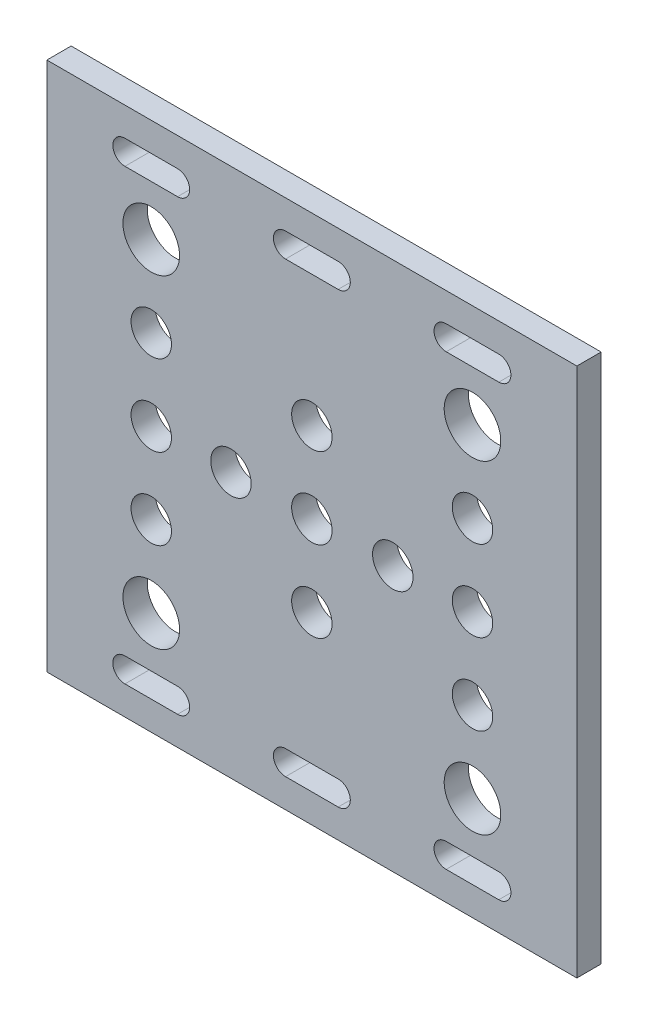
SolidWorks part; units mm, degrees
ref_plane "Front Plane" through (0, 0, 0) normal (0, 0, 1) x (1, 0, 0)
ref_plane "Top Plane" through (0, 0, 0) normal (0, 1, 0) x (1, 0, 0)
ref_plane "Right Plane" through (0, 0, 0) normal (1, 0, 0) x (0, 0, -1)
sketch "Sketch1" plane through (0, 0, 0) normal (0, 0, 1) x (1, 0, 0)
  line L0 (-32.75, -27.7) -> (32.75, -27.7) construction
  line L1 (-32.75, -32.75) -> (32.75, -32.75)
  line L2 (-32.75, -32.75) -> (-32.75, 32.75)
  line L3 (-32.75, 32.75) -> (32.75, 32.75)
  line L4 (32.75, -32.75) -> (32.75, 32.75)
  line L5 (-32.75, -32.75) -> (32.75, 32.75) construction
  line L6 (-32.75, 32.75) -> (32.75, -32.75) construction
  line L7 (-19.85, 32.75) -> (-19.85, -32.75) construction
  line L8 (0, 48.3783) -> (0, -50.4998) construction
  line L9 (-32.75, 27.7) -> (32.75, 27.7) construction
  line L10 (-23.1, 27.7) -> (-16.6, 27.7) construction
  line L11 (-23.1, 29.2) -> (-16.6, 29.2)
  line L12 (-23.1, 26.2) -> (-16.6, 26.2)
  line L13 (-32.75, 0) -> (32.75, 0) construction
  line L14 (-23.1, -27.7) -> (-16.6, -27.7) construction
  line L15 (-23.1, -26.2) -> (-16.6, -26.2)
  line L16 (-23.1, -29.2) -> (-16.6, -29.2)
  line L17 (-3.25, 27.7) -> (3.25, 27.7) construction
  line L18 (-3.25, 29.2) -> (3.25, 29.2)
  line L19 (-3.25, 26.2) -> (3.25, 26.2)
  line L20 (-3.25, -27.7) -> (3.25, -27.7) construction
  line L21 (-3.25, -29.2) -> (3.25, -29.2)
  line L22 (-3.25, -26.2) -> (3.25, -26.2)
  line L23 (23.1, -27.7) -> (16.6, -27.7) construction
  line L24 (23.1, -26.2) -> (16.6, -26.2)
  line L25 (23.1, -29.2) -> (16.6, -29.2)
  line L26 (23.1, 27.7) -> (16.6, 27.7) construction
  line L27 (23.1, 29.2) -> (16.6, 29.2)
  line L28 (23.1, 26.2) -> (16.6, 26.2)
  circle A0 centre (-19.85, 20) radius 3.5
  circle A1 centre (-19.85, 10) radius 2.5
  circle A2 centre (-19.85, 0) radius 2.5
  circle A3 centre (-19.85, -10) radius 2.5
  circle A4 centre (-19.85, -20) radius 3.5
  arc A5 (-23.1, 29.2) -> (-23.1, 26.2) centre (-23.1, 27.7) ccw
  arc A6 (-16.6, 26.2) -> (-16.6, 29.2) centre (-16.6, 27.7) ccw
  arc A7 (-23.1, -26.2) -> (-23.1, -29.2) centre (-23.1, -27.7) ccw
  arc A8 (-16.6, -29.2) -> (-16.6, -26.2) centre (-16.6, -27.7) ccw
  arc A9 (-3.25, 29.2) -> (-3.25, 26.2) centre (-3.25, 27.7) ccw
  arc A10 (3.25, 26.2) -> (3.25, 29.2) centre (3.25, 27.7) ccw
  arc A11 (-3.25, -29.2) -> (-3.25, -26.2) centre (-3.25, -27.7) cw
  arc A12 (3.25, -26.2) -> (3.25, -29.2) centre (3.25, -27.7) cw
  arc A13 (23.1, -26.2) -> (23.1, -29.2) centre (23.1, -27.7) cw
  arc A14 (16.6, -29.2) -> (16.6, -26.2) centre (16.6, -27.7) cw
  circle A15 centre (19.85, -20) radius 3.5
  circle A16 centre (19.85, -10) radius 2.5
  circle A17 centre (19.85, 0) radius 2.5
  circle A18 centre (19.85, 10) radius 2.5
  circle A19 centre (19.85, 20) radius 3.5
  arc A20 (23.1, 29.2) -> (23.1, 26.2) centre (23.1, 27.7) cw
  arc A21 (16.6, 26.2) -> (16.6, 29.2) centre (16.6, 27.7) cw
  circle A22 centre (0, 0) radius 2.5
  circle A23 centre (10, 0) radius 2.5
  circle A24 centre (-10, 0) radius 2.5
  circle A25 centre (0, 10) radius 2.5
  circle A26 centre (0, -10) radius 2.5
  point P0 (0, 0)
  point P24 (-19.85, 27.7)
  point P33 (-19.85, -27.7)
  point P40 (0, 27.7)
  point P50 (0, -27.7)
  point P57 (19.85, -27.7)
  point P74 (19.85, 27.7)
  dimension "D6" = 7
  dimension "D18" = 5
  dimension "D20" = 5
  dimension "D21" = 5
  dimension "D1" = 65.5
  dimension "D2" = 65.5
  dimension "D3" = 5.05
  dimension "D4" = 60.45
  dimension "D5" = 12.9
  dimension "D7" = 12.75
  dimension "D8" = 10
  dimension "D9" = 10
  dimension "D10" = 10
  dimension "D11" = 10
  dimension "D12" = 6.5
  dimension "D13" = 3
  dimension "D14" = 6.5
  dimension "D15" = 3
  dimension "D16" = 3
  dimension "D17" = 6.5
  dimension "D19" = 22.75
extrude "Boss-Extrude1" add sketch "Sketch1" along normal blind 3
